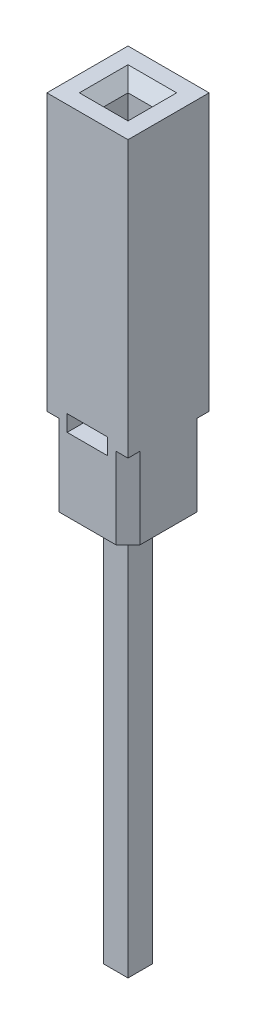
SolidWorks part; units mm, degrees
ref_plane "Plan de face" through (0, 0, 0) normal (0, 0, 1) x (1, 0, 0)
ref_plane "Plan de dessus" through (0, 0, 0) normal (0, 1, 0) x (1, 0, 0)
ref_plane "Plan de droite" through (0, 0, 0) normal (1, 0, 0) x (0, 0, -1)
ref_plane "Plan1" through (-1.27, 0, 0) normal (-1, 0, 0) x (0, -1, 0)
sketch "Esquisse1" plane through (-1.27, 0, 0) normal (-1, 0, 0) x (0, -1, 0)
  line L0 (-2.794, -1.27) -> (-2.794, 1.27)
  line L1 (-2.794, 1.27) -> (-11.176, 1.27)
  line L2 (-11.176, 1.27) -> (-11.176, -1.27)
  line L3 (-11.176, -1.27) -> (-2.794, -1.27)
extrude "Boss.-Extru.1" add sketch "Esquisse1" against normal blind 1.905
sketch "Esquisse2" plane through (0, 2.794, 0) normal (0, -1, 0) x (1, 0, 0)
  line L0 (-0.635, 1.27) -> (-0.635, -1.27)
  line L1 (-0.635, -1.27) -> (-1.27, -1.27)
  line L2 (-1.27, -1.27) -> (-1.27, 1.27)
  line L3 (-1.27, 1.27) -> (-0.635, 1.27)
extrude "Boss.-Extru.2" add sketch "Esquisse2" along normal blind 0.508
sketch "Esquisse3" plane through (0, 2.794, 0) normal (0, -1, 0) x (1, 0, 0)
  line L0 (0.381, -0.381) -> (-0.381, -0.381)
  line L1 (-0.381, -0.381) -> (-0.381, 0.381)
  line L2 (-0.381, 0.381) -> (0.381, 0.381)
  line L3 (0.381, 0.381) -> (0.381, -0.381)
extrude "Boss.-Extru.3" add sketch "Esquisse3" along normal blind 0.508
sketch "Esquisse4" plane through (0, 2.286, 0) normal (0, -1, 0) x (1, 0, 0)
  line L0 (0.635, 1.27) -> (0.635, -1.27)
  line L1 (0.635, -1.27) -> (-1.27, -1.27)
  line L2 (-1.27, -1.27) -> (-1.27, 1.27)
  line L3 (-1.27, 1.27) -> (0.635, 1.27)
extrude "Boss.-Extru.4" add sketch "Esquisse4" along normal blind 2.286
sketch "Esquisse5" plane through (0.635, 0, 0) normal (1, 0, 0) x (0, 0, -1)
  line L0 (1.27, 0) -> (-1.27, 0)
  line L1 (-1.27, 0) -> (-1.27, 11.176)
  line L2 (-1.27, 11.176) -> (1.27, 11.176)
  line L3 (1.27, 11.176) -> (1.27, 0)
extrude "Boss.-Extru.5" add sketch "Esquisse5" along normal blind 0.635
sketch "Esquisse6" plane through (0, 0, 0) normal (0, -1, 0) x (1, 0, 0)
  circle A0 centre (0, 0) radius 0.5388
extrude "Boss.-Extru.6" add sketch "Esquisse6" along normal blind 0.254
sketch "Esquisse7" plane through (0, -0.254, 0) normal (0, -1, 0) x (1, 0, 0)
  line L0 (0.381, -0.381) -> (-0.381, -0.381)
  line L1 (-0.381, -0.381) -> (-0.381, 0.381)
  line L2 (-0.381, 0.381) -> (0.381, 0.381)
  line L3 (0.381, 0.381) -> (0.381, -0.381)
extrude "Boss.-Extru.7" add sketch "Esquisse7" along normal blind 12.446
sketch "Esquisse8" plane through (0, 0, 0) normal (0, -1, 0) x (1, 0, 0)
  line L0 (-1.27, 1.27) -> (-1.27, 0.889)
  line L1 (-1.27, 0.889) -> (-0.889, 1.27)
  line L2 (-0.889, 1.27) -> (-1.27, 1.27)
extrude "Enlèv. mat.-Extru.1" cut sketch "Esquisse8" against normal blind 2.54
sketch "Esquisse9" plane through (0, 0, 0) normal (0, -1, 0) x (1, 0, 0)
  line L0 (-1.27, -1.27) -> (-0.889, -1.27)
  line L1 (-0.889, -1.27) -> (-1.27, -0.889)
  line L2 (-1.27, -0.889) -> (-1.27, -1.27)
extrude "Enlèv. mat.-Extru.2" cut sketch "Esquisse9" against normal blind 2.54
sketch "Esquisse10" plane through (0, 0, 0) normal (0, -1, 0) x (1, 0, 0)
  line L0 (1.27, 1.27) -> (0.889, 1.27)
  line L1 (0.889, 1.27) -> (1.27, 0.889)
  line L2 (1.27, 0.889) -> (1.27, 1.27)
extrude "Enlèv. mat.-Extru.3" cut sketch "Esquisse10" against normal blind 2.54
sketch "Esquisse11" plane through (0, 0, 0) normal (0, -1, 0) x (1, 0, 0)
  line L0 (1.27, -1.27) -> (1.27, -0.889)
  line L1 (1.27, -0.889) -> (0.889, -1.27)
  line L2 (0.889, -1.27) -> (1.27, -1.27)
extrude "Enlèv. mat.-Extru.4" cut sketch "Esquisse11" against normal blind 2.54
sketch "Esquisse12" plane through (0, 11.176, 0) normal (0, 1, 0) x (-1, 0, 0)
  line L0 (-0.381, 0.381) -> (-0.381, -0.381)
  line L1 (-0.381, -0.381) -> (0.381, -0.381)
  line L2 (0.381, -0.381) -> (0.381, 0.381)
  line L3 (0.381, 0.381) -> (-0.381, 0.381)
extrude "Enlèv. mat.-Extru.5" cut sketch "Esquisse12" against normal blind 7.62
chamfer "Chanfrein1" distance 0.254 angle 45 4 edges at (0, -12.7, 0.381) (0.381, -12.7, 0) (-0.381, -12.7, 0) (0, -12.7, -0.381)
chamfer "Chanfrein2" distance 0.381 angle 45 4 edges at (-0.381, 11.176, 0) (0, 11.176, -0.381) (0, 11.176, 0.381) (0.381, 11.176, 0)
